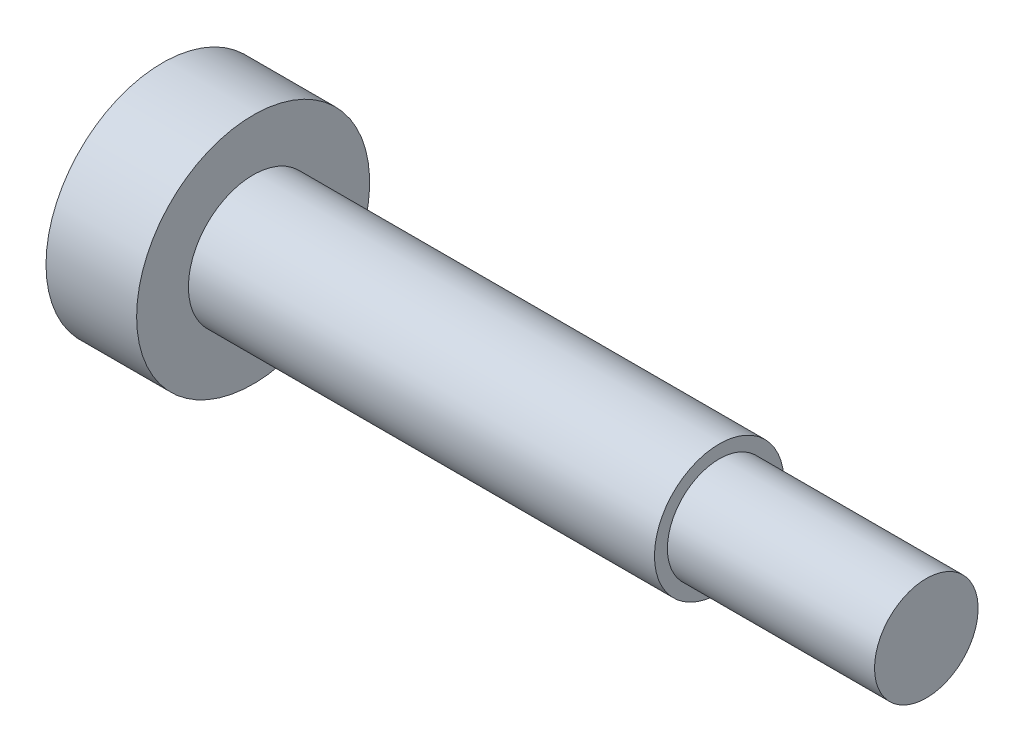
SolidWorks part; units mm, degrees
ref_plane "Front Plane" through (0, 0, 0) normal (0, 0, 1) x (1, 0, 0)
ref_plane "Top Plane" through (0, 0, 0) normal (0, 1, 0) x (1, 0, 0)
ref_plane "Right Plane" through (0, 0, 0) normal (1, 0, 0) x (0, 0, -1)
sketch "Sketch1" plane through (0, 0, 0) normal (0, 1, 0) x (1, 0, 0)
  line L0 (0, 0) -> (0, 2)
  line L1 (0, 2) -> (-8, 2)
  line L2 (-8, 2) -> (-8, 2.5)
  line L3 (-8, 2.5) -> (-26, 2.5)
  line L4 (-26, 2.5) -> (-26, 4.5)
  line L5 (-26, 4.5) -> (-29.5, 4.5)
  line L6 (-29.5, 4.5) -> (-29.5, 0)
  line L7 (-29.5, 0) -> (0, 0)
  dimension "D1" = 2
  dimension "D2" = 8
  dimension "D3" = 0.5
  dimension "D4" = 4.5
  dimension "D5" = 3.5
  dimension "D6" = 18
revolve "Revolve1" add sketch "Sketch1" angle 360 about L7
equation "\"BASE_R\"= 2"
equation "\"D1@Sketch1\"=\"BASE_R\""
equation "\"BASE_L\"= 8"
equation "\"D2@Sketch1\"=\"BASE_L\""
equation "\"BEAR_ADD_R\"=0.5"
equation "\"D3@Sketch1\"=\"BEAR_ADD_R\""
equation "\"HEAD_R\"= 4.5"
equation "\"D4@Sketch1\"=\"HEAD_R\""
equation "\"HEAD_L\"= 3.5"
equation "\"D5@Sketch1\"=\"HEAD_L\""
equation "\"BEAR_L\"= 18"
equation "\"D6@Sketch1\"=\"BEAR_L\""
